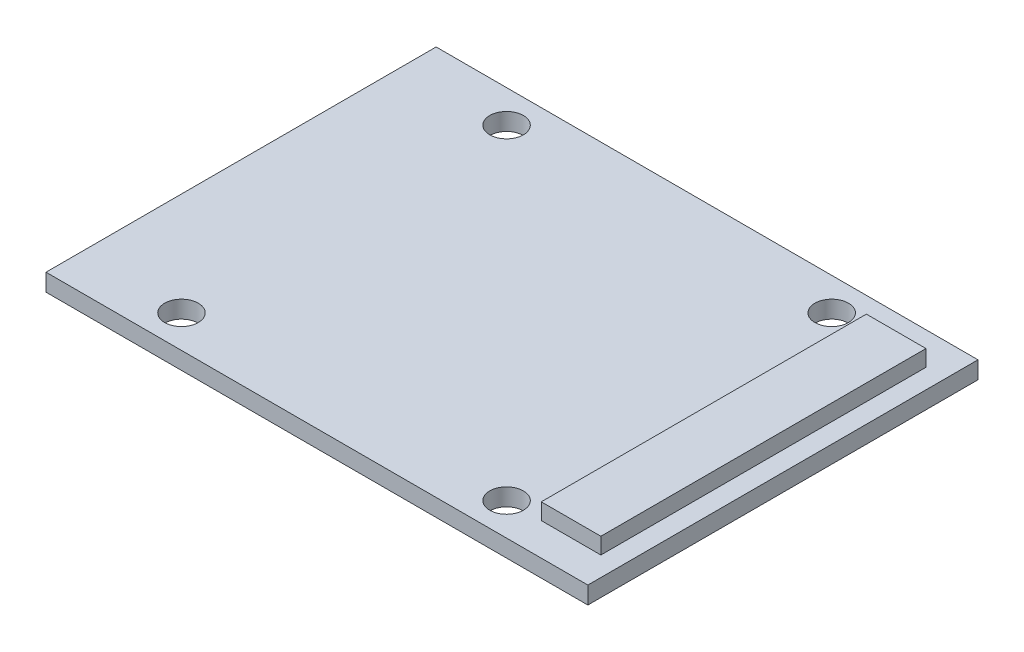
SolidWorks part; units mm, degrees
ref_plane "Front Plane" through (0, 0, 0) normal (0, 0, 1) x (1, 0, 0)
ref_plane "Top Plane" through (0, 0, 0) normal (0, 1, 0) x (1, 0, 0)
ref_plane "Right Plane" through (0, 0, 0) normal (1, 0, 0) x (0, 0, -1)
sketch "Sketch1" plane through (0, 0, 0) normal (0, 1, 0) x (1, 0, 0)
  line L0 (-25, 0) -> (25, 0) construction
  line L1 (25, 18) -> (-25, 18)
  line L2 (25, 18) -> (25, -18)
  line L3 (25, -18) -> (-25, -18)
  line L4 (-25, 18) -> (-25, -18)
  line L5 (25, 18) -> (-25, -18) construction
  line L6 (25, -18) -> (-25, 18) construction
  circle A0 centre (-15.5, 15) radius 1.55
  circle A1 centre (-15.5, -15) radius 1.55
  circle A2 centre (14.5, 15) radius 1.55
  circle A3 centre (14.5, -15) radius 1.55
  point P0 (0, 0)
  dimension "D3" = 3.1
  dimension "D1" = 50
  dimension "D2" = 36
  dimension "D4" = 9.5
  dimension "D5" = 3
  dimension "D6" = 10.5
extrude "Boss-Extrude1" add sketch "Sketch1" along normal blind 1.6
sketch "Sketch2" plane through (0, 1.6, 0) normal (0, 1, 0) x (1, 0, 0)
  line L0 (23.2, 0) -> (17.7, 0) construction
  line L1 (23.2, 15) -> (17.7, 15)
  line L2 (23.2, 15) -> (23.2, -15)
  line L3 (23.2, -15) -> (17.7, -15)
  line L4 (17.7, 15) -> (17.7, -15)
  line L5 (25, 0) -> (-25, 0) construction
  line L6 (25, -18) -> (25, 18) construction
  line L7 (-25, 18) -> (-25, -18) construction
  dimension "D1" = 5.5
  dimension "D2" = 30
  dimension "D3" = 1.8
extrude "Boss-Extrude2" add sketch "Sketch2" along normal blind 1.5
